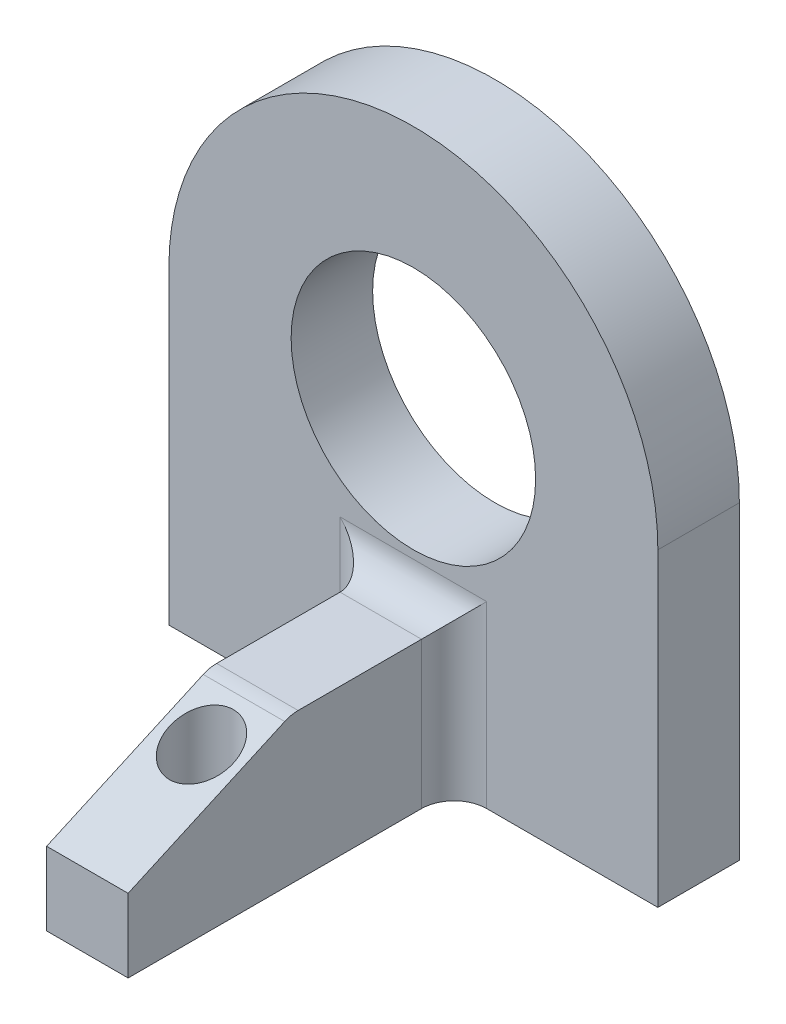
SolidWorks part; units mm, degrees
material "6061-T6 (SS)"
ref_plane "Front Plane" through (0, 0, 0) normal (0, 0, 1) x (1, 0, 0)
ref_plane "Top Plane" through (0, 0, 0) normal (0, 1, 0) x (1, 0, 0)
ref_plane "Right Plane" through (0, 0, 0) normal (1, 0, 0) x (0, 0, -1)
sketch "Sketch1" plane through (0, 0, 0) normal (0, 0, 1) x (1, 0, 0)
  line L0 (0, 0) -> (0, 14.605) construction
  line L1 (0, 14.605) -> (0, 33.655) construction
  line L2 (-19.05, 24.13) -> (-19.05, 14.605)
  line L3 (-19.05, 0) -> (19.05, 0)
  line L4 (-19.05, 0) -> (-19.05, 14.605)
  line L5 (-19.05, 14.605) -> (19.05, 14.605)
  line L6 (19.05, 0) -> (19.05, 14.605)
  line L7 (-19.05, 0) -> (19.05, 14.605) construction
  line L8 (-19.05, 14.605) -> (19.05, 0) construction
  line L9 (19.05, 14.605) -> (19.05, 24.13)
  circle A0 centre (0, 24.13) radius 9.525
  circle A1 centre (0, 24.13) radius 19.05
  point P6 (0, 7.3025)
  point P13 (0, 0)
  dimension "D1" = 24.13
  dimension "D2" = 19.05
  dimension "D3" = 38.1
extrude "Boss-Extrude1" add sketch "Sketch1" along normal blind 6.35 contours A1 L5 A0 | A1 L2 L5 | L5 A1 | A1 L5 L9 | A1 L5 L4 L3 L6
sketch "Sketch2" plane through (0, 0, 6.35) normal (0, 0, 1) x (1, 0, 0)
  line L0 (0, 0) -> (0, 11.43) construction
  line L1 (-19.05, 0) -> (19.05, 0) construction
  line L3 (-3.175, 0) -> (3.175, 0)
  line L4 (-3.175, 0) -> (-3.175, 11.43)
  line L5 (-3.175, 11.43) -> (3.175, 11.43)
  line L6 (3.175, 0) -> (3.175, 11.43)
  line L7 (-3.175, 0) -> (3.175, 11.43) construction
  line L8 (-3.175, 11.43) -> (3.175, 0) construction
  circle A0 centre (0, 24.13) radius 9.525 construction
  point P4 (0, 5.715)
  dimension "D1" = 12.7
  dimension "D2" = 6.35
extrude "Boss-Extrude2" add sketch "Sketch2" along normal blind 25.4
sketch "Sketch3" plane through (3.175, 0, 0) normal (1, 0, 0) x (0, 0, -1)
  line L0 (-6.35, 11.43) -> (-31.75, 11.43)
  line L1 (-31.75, 11.43) -> (-31.75, 5.715)
  line L2 (-31.75, 5.715) -> (-19.05, 11.43)
  line L3 (-31.75, 0) -> (-31.75, 11.43) construction
  line M3 (-31.75, 11.43) -> (-31.75, 0)
extrude "Cut-Extrude1" cut sketch "Sketch3" against normal blind 25.4 contours L2 L0 M3
sketch "Sketch4" plane through (0, 0, 0) normal (0, -1, 0) x (1, 0, 0)
  line L0 (-19.05, 3.175) -> (0, 3.175) construction
  line L1 (-19.05, 6.35) -> (-19.05, 0) construction
  line L2 (0, 3.175) -> (19.05, 3.175) construction
  line L3 (19.05, 6.35) -> (19.05, 0) construction
  line L4 (0, 1.27) -> (0, 3.175) construction
  line L5 (-3.175, 44.45) -> (3.175, 44.45) construction
  line L6 (0, 1.27) -> (0, 44.45) construction
  line L7 (-3.175, 31.75) -> (3.175, 31.75) construction
  circle A0 centre (-9.525, 3.175) radius 2.4892
  circle A1 centre (9.525, 3.175) radius 2.4892
  circle A2 centre (0, 22.86) radius 2.4892
  dimension "D1" = 4.9784
  dimension "D2" = 8.89
extrude "Cut-Extrude2" cut sketch "Sketch4" against normal blind 12.7
fillet "Fillet1" radius 2.54 4 edges at (0, 11.43, 19.05) (0, 11.43, 6.35)
